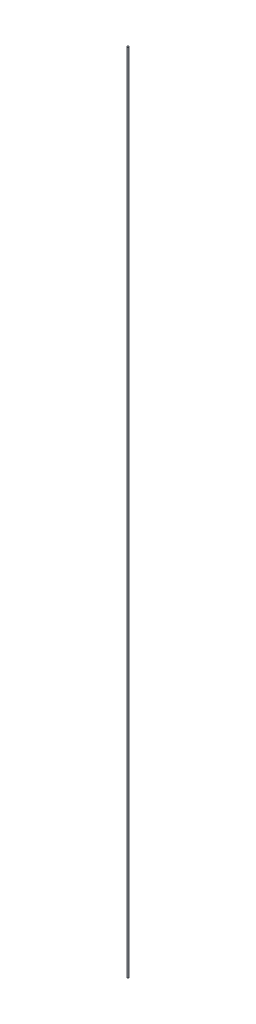
SolidWorks part; units mm, degrees
ref_plane "Plan de face" through (0, 0, 0) normal (0, 0, 1) x (1, 0, 0)
ref_plane "Plan de dessus" through (0, 0, 0) normal (0, 1, 0) x (1, 0, 0)
ref_plane "Plan de droite" through (0, 0, 0) normal (1, 0, 0) x (0, 0, -1)
sketch "Esquisse1" plane through (0, 0, 0) normal (0, 1, 0) x (1, 0, 0)
  circle A0 centre (0, 0) radius 0.5
extrude "Boss.-Extru.1" add sketch "Esquisse1" along normal blind 580
sketch "Esquisse2" plane through (0, 580, 0) normal (0, 1, 0) x (1, 0, 0)
  circle A0 centre (0, 0) radius 0.5
extrude "Enlèv. mat.-Extru.2" cut sketch "Esquisse2" against normal blind 80
